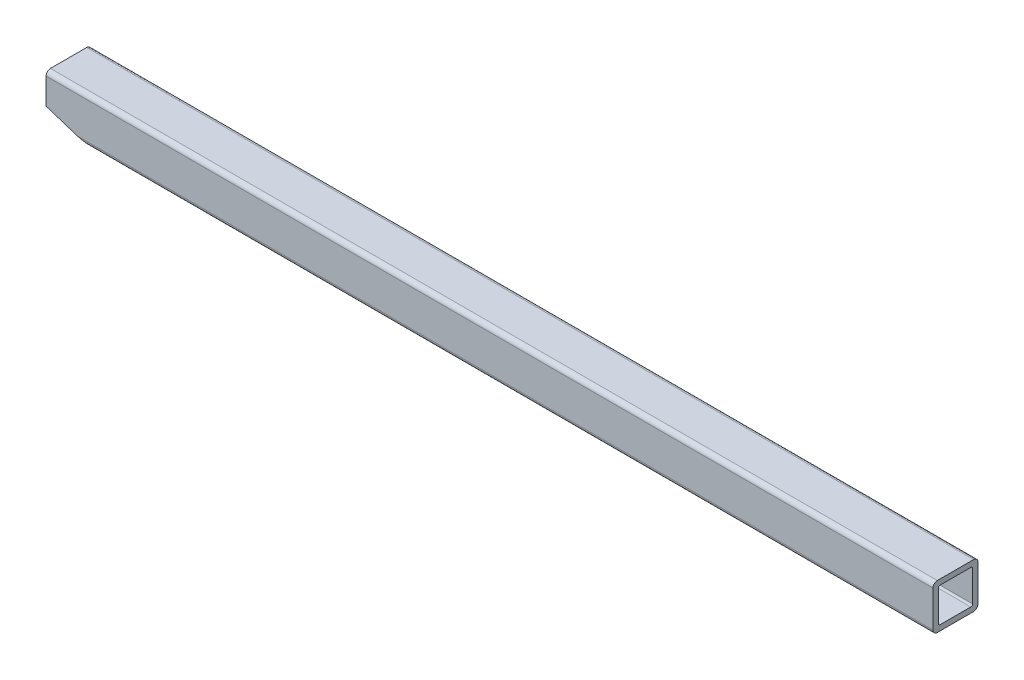
SolidWorks part; units mm, degrees
ref_plane "Front Plane" through (0, 0, 0) normal (0, 0, 1) x (1, 0, 0)
ref_plane "Top Plane" through (0, 0, 0) normal (0, 1, 0) x (1, 0, 0)
ref_plane "Right Plane" through (0, 0, 0) normal (1, 0, 0) x (0, 0, -1)
sketch "Sketch3" plane through (0, 0, 0) normal (1, 0, 0) x (0, 0, -1)
  line L1 (-12.7, 12.7) -> (12.7, 12.7)
  line L2 (-12.7, 12.7) -> (-12.7, -12.7)
  line L3 (-12.7, -12.7) -> (12.7, -12.7)
  line L4 (12.7, 12.7) -> (12.7, -12.7)
  line L5 (-12.7, 12.7) -> (12.7, -12.7) construction
  line L6 (-12.7, -12.7) -> (12.7, 12.7) construction
  line L7 (-9.652, -9.652) -> (9.652, -9.652)
  line L8 (-9.652, -9.652) -> (-9.652, 9.652)
  line L9 (-9.652, 9.652) -> (9.652, 9.652)
  line L10 (9.652, -9.652) -> (9.652, 9.652)
  line L11 (-9.652, -9.652) -> (9.652, 9.652) construction
  line L12 (-9.652, 9.652) -> (9.652, -9.652) construction
  point P0 (0, 0)
  point P6 (0, 0)
  dimension "D1" = 25.4
  dimension "D2" = 19.304
  dimension "D3" = 19.304
  dimension "D4" = 25.4
extrude "Boss-Extrude1" add sketch "Sketch3" against normal blind 500
fillet "Fillet1" radius 2.5 4 edges at (-250, -12.7, -12.7) (-250, -12.7, 12.7) (-250, 12.7, -12.7) (-250, 12.7, 12.7)
fillet "Fillet2" radius 1 4 edges at (-250, -9.652, -9.652) (-250, 9.652, -9.652) (-250, 9.652, 9.652) (-250, -9.652, 9.652)
sketch "Sketch4" plane through (0, 0, 12.7) normal (0, 0, 1) x (1, 0, 0)
  line L0 (-500, 12.6499) -> (-500, -4.45)
  line L1 (-500, 12.7) -> (-500, 10.2) construction
  line L2 (-500, 10.2) -> (-500, -10.2) construction
  line L3 (-500, -4.45) -> (-474.6091, -12.7)
  line L4 (0, -12.7) -> (-500, -12.7) construction
  line L5 (-474.6091, -12.7) -> (-500, -12.7)
  line L6 (-500, -12.7) -> (-500, -4.45)
  line M4 (-500, 10.2) -> (-500, -10.2)
  line M5 (-500, -10.2) -> (0, -10.2)
  dimension "D1" = 18
  dimension "D2" = 8.25
extrude "Cut-Extrude1" cut sketch "Sketch4" against normal through all contours L3 M4 M5 | L6 L5 L3 M5
